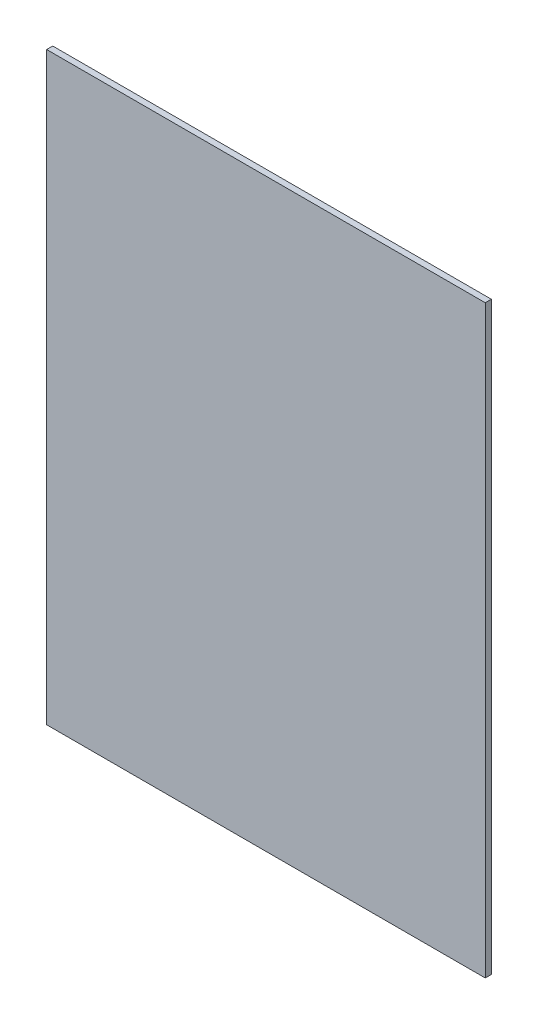
SolidWorks part; units mm, degrees
material "Acrylic (Medium-high impact)"
ref_plane "Front Plane" through (0, 0, 0) normal (0, 0, 1) x (1, 0, 0)
ref_plane "Top Plane" through (0, 0, 0) normal (0, 1, 0) x (1, 0, 0)
ref_plane "Right Plane" through (0, 0, 0) normal (1, 0, 0) x (0, 0, -1)
sketch "Sketch1" plane through (0, 0, 0) normal (0, 0, 1) x (1, 0, 0)
  line L1 (-114.3, 152.4) -> (114.3, 152.4)
  line L2 (-114.3, 152.4) -> (-114.3, -152.4)
  line L3 (-114.3, -152.4) -> (114.3, -152.4)
  line L4 (114.3, 152.4) -> (114.3, -152.4)
  line L5 (-114.3, 152.4) -> (114.3, -152.4) construction
  line L6 (-114.3, -152.4) -> (114.3, 152.4) construction
  point P0 (0, 0)
  dimension "D1" = 304.8
  dimension "D2" = 228.6
extrude "Boss-Extrude1" add sketch "Sketch1" along normal blind 3.175 contours L1 L4 L3 L2
